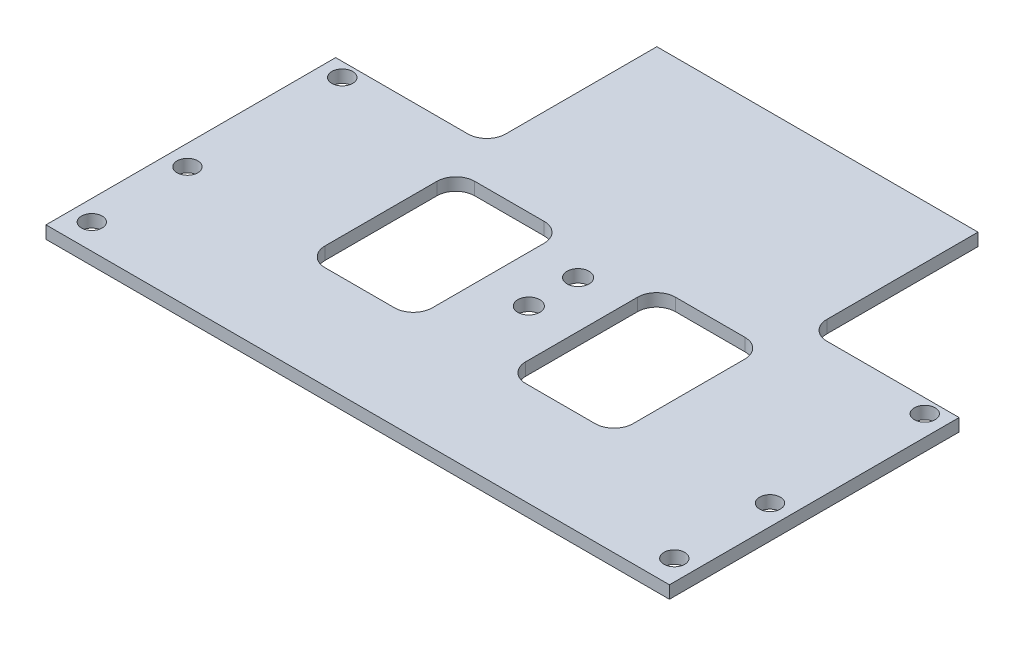
SolidWorks part; units mm, degrees
ref_plane "Alzado" through (0, 0, 0) normal (0, 0, 1) x (1, 0, 0)
ref_plane "Planta" through (0, 0, 0) normal (0, 1, 0) x (1, 0, 0)
ref_plane "Vista lateral" through (0, 0, 0) normal (1, 0, 0) x (0, 0, -1)
sketch "Croquis1" plane through (0, 0, 0) normal (0, 1, 0) x (1, 0, 0)
  line L0 (-49.5, 9.5) -> (-28.5, 9.5)
  line L1 (-49.5, 36.5) -> (49.5, 36.5)
  line L2 (-49.5, 36.5) -> (-49.5, -36.5)
  line L3 (-49.5, -36.5) -> (49.5, -36.5)
  line L4 (49.5, 36.5) -> (49.5, -36.5)
  line L5 (-49.5, 36.5) -> (49.5, -36.5) construction
  line L6 (-49.5, -36.5) -> (49.5, 36.5) construction
  line L7 (-25.5, 12.5) -> (-25.5, 36.5)
  line L8 (0, 0) -> (0, -18.4798) construction
  line L9 (25.5, 12.5) -> (25.5, 36.5)
  line L10 (49.5, 9.5) -> (28.5, 9.5)
  line L11 (-7.417, 0.5305) -> (-7.417, -17.238)
  line L12 (21.4508, 3.5305) -> (10.417, 3.5305)
  line L13 (24.4508, 0.5305) -> (24.4508, -17.238)
  line L14 (21.4508, -20.238) -> (10.417, -20.238)
  line L15 (7.417, 0.5305) -> (7.417, -17.238)
  line L16 (-24.4508, 0.5305) -> (-24.4508, -17.238)
  line L17 (-21.4508, -20.238) -> (-10.417, -20.238)
  line L18 (-21.4508, 3.5305) -> (-10.417, 3.5305)
  circle A2 centre (0, -1.5041) radius 1.75
  circle A3 centre (0, -9.3293) radius 1.75
  circle A4 centre (46.25, 7.2945) radius 1.65
  circle A5 centre (46.25, -32.4743) radius 1.65
  circle A6 centre (46.25, -17.2861) radius 1.65
  circle A7 centre (-46.25, -17.2861) radius 1.65
  circle A8 centre (-46.25, -32.4743) radius 1.65
  circle A9 centre (-46.25, 7.2945) radius 1.65
  arc A10 (-25.5, 12.5) -> (-28.5, 9.5) centre (-28.5, 12.5) cw
  arc A11 (25.5, 12.5) -> (28.5, 9.5) centre (28.5, 12.5) ccw
  arc A12 (7.417, -17.238) -> (10.417, -20.238) centre (10.417, -17.238) ccw
  arc A13 (24.4508, -17.238) -> (21.4508, -20.238) centre (21.4508, -17.238) cw
  arc A14 (10.417, 3.5305) -> (7.417, 0.5305) centre (10.417, 0.5305) ccw
  arc A15 (21.4508, 3.5305) -> (24.4508, 0.5305) centre (21.4508, 0.5305) cw
  arc A16 (-7.417, -17.238) -> (-10.417, -20.238) centre (-10.417, -17.238) cw
  arc A17 (-10.417, 3.5305) -> (-7.417, 0.5305) centre (-10.417, 0.5305) cw
  arc A18 (-21.4508, 3.5305) -> (-24.4508, 0.5305) centre (-21.4508, 0.5305) ccw
  arc A19 (-24.4508, -17.238) -> (-21.4508, -20.238) centre (-21.4508, -17.238) ccw
  point P0 (0, 0)
  point P40 (-25.5, 9.5)
  point P43 (25.5, 9.5)
  dimension "D5" = 3.5
  dimension "D6" = 3.5
  dimension "D7" = 3
  dimension "D9" = 3.3
  dimension "D10" = 3.3
  dimension "D11" = 3.3
  dimension "D1" = 73
  dimension "D2" = 99
  dimension "D3" = 27
  dimension "D4" = 24
extrude "Saliente-Extruir1" add sketch "Croquis1" along normal blind 2 contours L4 L10 L9 L1 L7 L0 L2 L3
